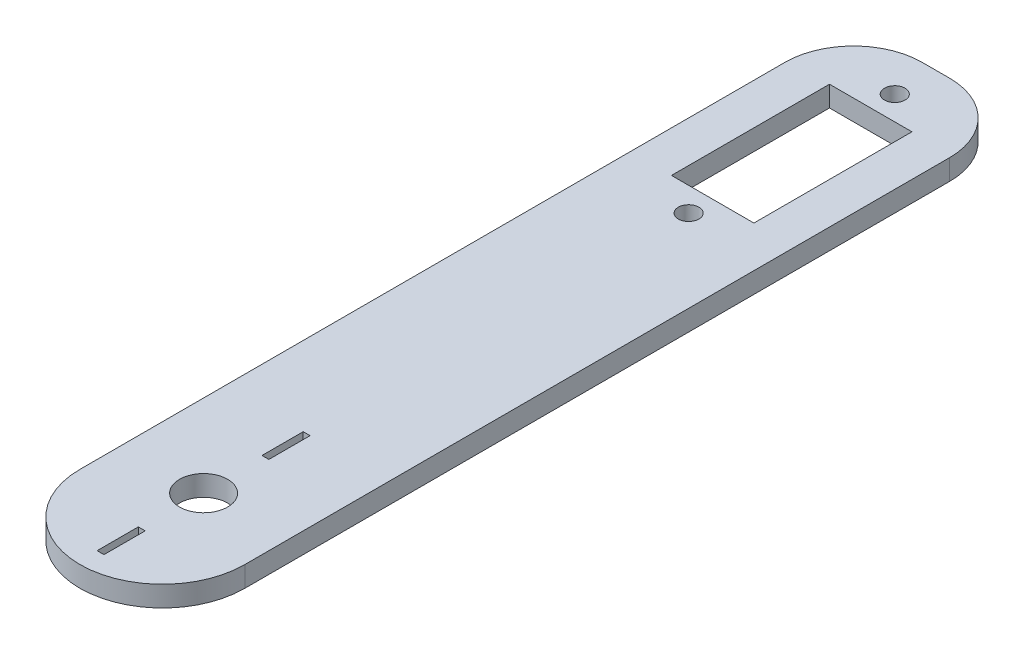
SolidWorks part; units mm, degrees
material "Pinho"
ref_plane "Plano frontal" through (0, 0, 0) normal (0, 0, 1) x (1, 0, 0)
ref_plane "Plano superior" through (0, 0, 0) normal (0, 1, 0) x (1, 0, 0)
ref_plane "Plano direito" through (0, 0, 0) normal (1, 0, 0) x (0, 0, -1)
sketch "Esboço4" plane through (0, 0, 0) normal (0, 1, 0) x (1, 0, 0)
  line L0 (-11.9874, 71.4666) -> (-11.9874, -8.6334)
  line L1 (6.0126, 71.4666) -> (-5.9874, 71.4666)
  line L2 (12.0126, 71.4666) -> (12.0126, -8.6334)
  line L3 (6.0126, 94.4666) -> (2.5, 94.4666)
  line L4 (-5.9874, 94.4666) -> (-2.5, 94.4666)
  line L7 (0.0126, -17.6334) -> (-0.4874, -17.6334)
  line L8 (-0.4874, -17.6334) -> (-0.4874, -11.6334)
  line L9 (-0.4874, -11.6334) -> (0.5126, -11.6334)
  line L10 (0.5126, -11.6334) -> (0.5126, -17.6334)
  line L11 (0.5126, -17.6334) -> (0.0126, -17.6334)
  line L12 (0.5126, 12.3666) -> (0.0126, 12.3666)
  line L13 (0.5126, 6.3666) -> (0.5126, 12.3666)
  line L14 (-0.4874, 6.3666) -> (0.5126, 6.3666)
  line L15 (-0.4874, 12.3666) -> (-0.4874, 6.3666)
  line L16 (0.0126, 12.3666) -> (-0.4874, 12.3666)
  line L34 (0.0126, 103.9666) -> (2.0126, 103.9666)
  line L35 (-1.9874, 103.9666) -> (0.0126, 103.9666)
  line L38 (12.0126, 71.4666) -> (12.0126, 93.9666)
  line L39 (-5.9874, 82.9666) -> (-5.9874, 94.4666)
  line L40 (-5.9874, 82.9666) -> (-5.9874, 71.4666)
  line L41 (6.0126, 71.4666) -> (6.0126, 94.4666)
  line L42 (-11.9874, 71.4666) -> (-11.9874, 93.9666)
  line L43 (-5.9874, 71.4666) -> (-2.4874, 71.4666)
  line L44 (6.0126, 71.4666) -> (2.4874, 71.4666)
  line L45 (6.0126, 94.4666) -> (-5.9874, 94.4666)
  line L46 (2.4874, 71.4666) -> (-2.4874, 71.4666)
  circle A0 centre (0.0126, -2.6334) radius 3.5
  arc A1 (-11.9874, -8.6334) -> (12.0126, -8.6334) centre (0.0126, -8.6334) ccw
  arc A12 (12.0126, 93.9666) -> (2.0126, 103.9666) centre (2.0126, 93.9666) ccw
  circle A13 centre (0.0126, 97.9666) radius 1.5
  arc A14 (-11.9874, 93.9666) -> (-1.9874, 103.9666) centre (-1.9874, 93.9666) cw
  circle A15 centre (0.0126, 67.9667) radius 1.5
extrude "Ressalto-extrusão1" add sketch "Esboço4" along normal blind 3 contours A14 L42 L0 A1 L2 L38 A12 L34 L35 A13 A0 L45 L3 L41 L1 L40 L39 L4 L16 L12 L13 L14 L15 L10 L11 L7 L8 L9 A15
